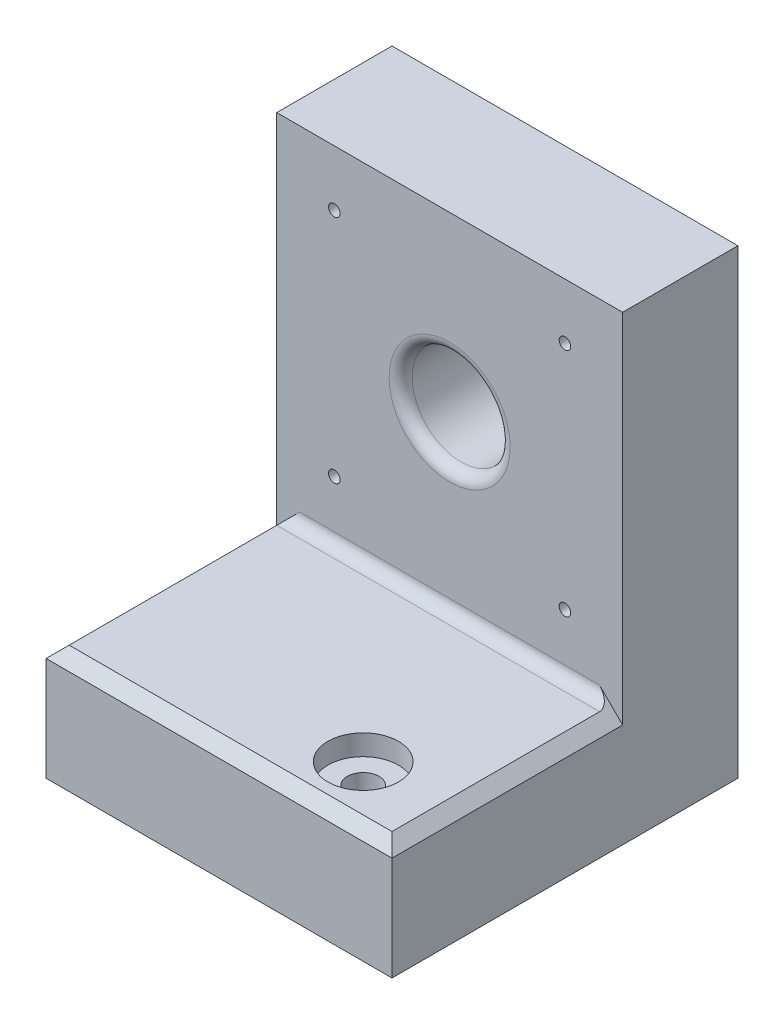
SolidWorks part; units mm, degrees
ref_plane "Front" through (0, 0, 0) normal (0, 0, 1) x (1, 0, 0)
ref_plane "Top" through (0, 0, 0) normal (0, 1, 0) x (1, 0, 0)
ref_plane "Right" through (0, 0, 0) normal (1, 0, 0) x (0, 0, -1)
sketch "Sketch1" plane through (0, 0, 0) normal (1, 0, 0) x (0, 0, -1)
  line L0 (0, 0) -> (0, 80)
  line L1 (0, 80) -> (-20, 80)
  line L2 (-20, 80) -> (-20, 20)
  line L3 (-20, 20) -> (-60, 20)
  line L6 (0, 0) -> (-60, 0)
  line L7 (-60, 0) -> (-60, 20)
  dimension "D1" = 60
  dimension "D2" = 80
  dimension "D3" = 20
  dimension "D4" = 20
extrude "Boss-Extrude1" add sketch "Sketch1" along normal blind 60
sketch "Sketch2" plane through (0, 0, 20) normal (0, 0, 1) x (1, 0, 0)
  line L0 (0, 80) -> (30, 80) construction
  line L1 (60, 80) -> (0, 80) construction
  line L2 (30, 80) -> (30, 50) construction
  circle A0 centre (30, 50) radius 8.5
  dimension "D3" = 17
  dimension "D1" = 30
  dimension "D2" = 30
extrude "Cut-Extrude1" cut sketch "Sketch2" against normal through all
fillet "Fillet1" radius 2 2 edges at (38.5, 50, 20) (38.5, 50, 0)
sketch "Sketch3" plane through (0, 0, 20) normal (0, 0, 1) x (1, 0, 0)
  line L0 (0, 80) -> (10, 80) construction
  line L1 (60, 80) -> (0, 80) construction
  line L2 (10, 80) -> (10, 70.339) construction
  line L3 (10, 70.339) -> (50, 70.339) construction
  line L4 (50, 70.339) -> (50, 30.339) construction
  line L5 (10, 70.339) -> (10, 30.339) construction
  line L6 (10, 30.339) -> (50, 30.339) construction
  circle A0 centre (10, 70.339) radius 1
  circle A1 centre (50, 70.339) radius 1
  circle A2 centre (50, 30.339) radius 1
  circle A3 centre (10, 30.339) radius 1
  dimension "D4" = 2
  dimension "D5" = 9.661
  dimension "D6" = 10
  dimension "D7" = 40
  dimension "D1" = 2
  dimension "D2" = 2
  dimension "D3" = 2
extrude "Cut-Extrude2" cut sketch "Sketch3" against normal blind 10
sketch "Sketch5" plane through (0, 20, 0) normal (0, 1, 0) x (1, 0, 0)
  line L0 (60, -60) -> (60, -50) construction
  line L1 (60, -20) -> (60, -60) construction
  line L2 (60, -50) -> (45, -50) construction
  circle A0 centre (45, -50) radius 6.12
  dimension "D3" = 12.24
  dimension "D1" = 10
  dimension "D2" = 15
extrude "Cut-Extrude3" cut sketch "Sketch5" against normal blind 3.58
sketch "Sketch6" plane through (0, 16.42, 0) normal (0, 1, 0) x (1, 0, 0)
  circle A0 centre (45, -50) radius 2.75
  dimension "D1" = 5.5
extrude "Cut-Extrude4" cut sketch "Sketch6" against normal through all
chamfer "Chamfer1" distance 2 angle 45 3 edges at (60, 20, 40) (0, 20, 40) (30, 20, 60)
fillet "Fillet2" radius 2 1 edges at (30, 20, 20)
